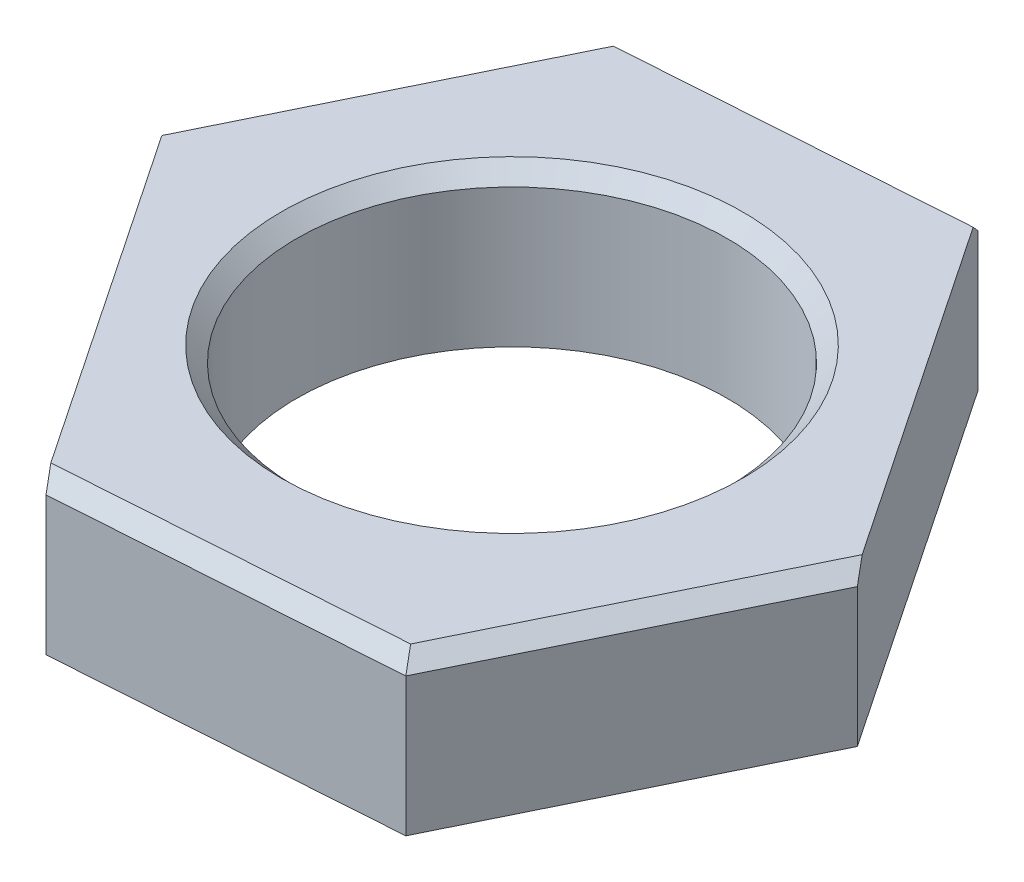
SolidWorks part; units mm, degrees
ref_plane "Front Plane" through (0, 0, 0) normal (0, 0, 1) x (1, 0, 0)
ref_plane "Top Plane" through (0, 0, 0) normal (0, 1, 0) x (1, 0, 0)
ref_plane "Right Plane" through (0, 0, 0) normal (1, 0, 0) x (0, 0, -1)
sketch "Sketch1" plane through (0, 0, 0) normal (0, 1, 0) x (1, 0, 0)
  line L1 (7.0886, -10.5397) -> (12.6719, 0.8691)
  line L2 (12.6719, 0.8691) -> (5.5833, 11.4088)
  line L3 (5.5833, 11.4088) -> (-7.0886, 10.5397)
  line L4 (-7.0886, 10.5397) -> (-12.6719, -0.8691)
  line L5 (-12.6719, -0.8691) -> (-5.5833, -11.4088)
  line L6 (-5.5833, -11.4088) -> (7.0886, -10.5397)
  circle A0 centre (0, 0) radius 11 construction
  circle A1 centre (0, 0) radius 7
extrude "Boss-Extrude1" add sketch "Sketch1" along normal blind 5
chamfer "Chamfer1" distance 0.5 angle 45 7 edges at (0, 5, 7) (-9.1276, 5, 6.1389) (-9.8803, 5, -4.8353) (-0.7527, 5, -10.9742) (9.1276, 5, -6.1389) (9.8803, 5, 4.8353) (0.7527, 5, 10.9742)
sketch "Sketch2" plane through (0, 5, 0) normal (0, 1, 0) x (1, 0, 0)
  line L0 (-12.3698, 1.3695) -> (-3.3134, -12.0959)
  line L1 (-12.0959, -0.8296) -> (-5.3295, -10.8902) construction
  line L2 (-12.3698, 1.3695) -> (-15.2781, -0.5865)
  line L3 (-15.2781, -0.5865) -> (-6.2217, -14.0519)
  line L4 (-6.2217, -14.0519) -> (-3.3134, -12.0959)
  line L5 (0, 0) -> (-8.8133, 13.104) construction
  line L6 (3.3961, 11.9731) -> (6.3043, 13.9291)
  line L7 (6.3043, 13.9291) -> (15.3607, 0.4637)
  line L8 (15.3607, 0.4637) -> (12.4524, -1.4923)
  line L9 (3.3961, 11.9731) -> (12.4524, -1.4923)
  dimension "D1" = 9.5
extrude "Cut-Extrude1" cut sketch "Sketch2" against normal through all
